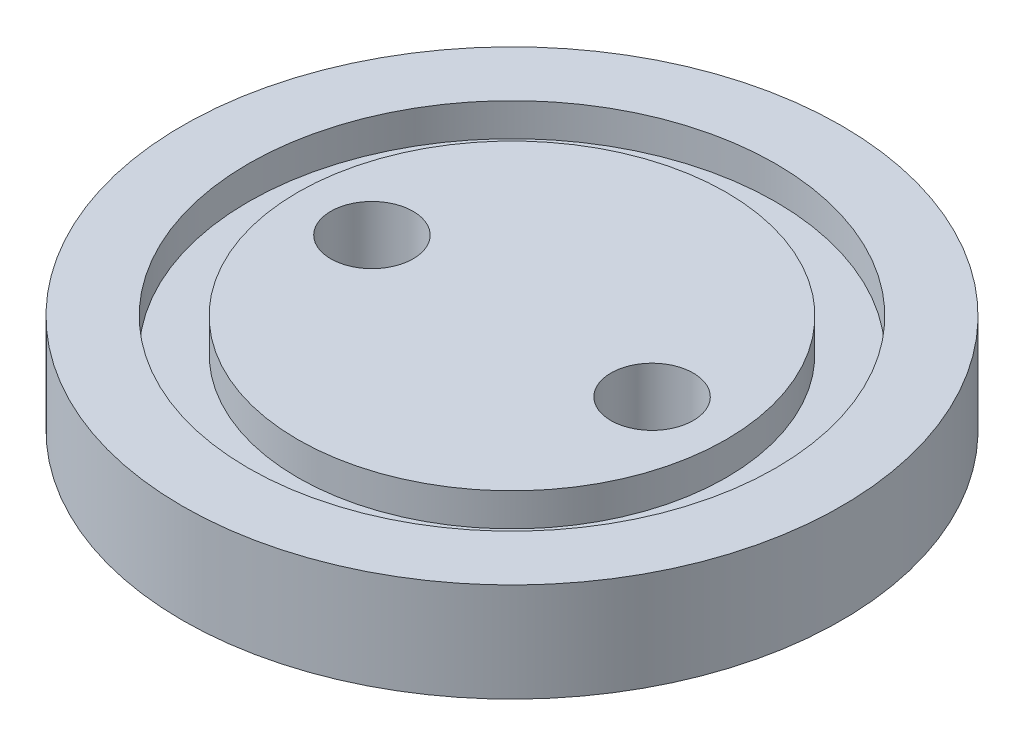
SolidWorks part; units mm, degrees
ref_plane "Front Plane" through (0, 0, 0) normal (0, 0, 1) x (1, 0, 0)
ref_plane "Top Plane" through (0, 0, 0) normal (0, 1, 0) x (1, 0, 0)
ref_plane "Right Plane" through (0, 0, 0) normal (1, 0, 0) x (0, 0, -1)
sketch "Sketch1" plane through (0, 0, 0) normal (0, 1, 0) x (1, 0, 0)
  line L0 (0, 6.5) -> (0, -6.5) construction
  circle A0 centre (0, 0) radius 10
  dimension "D1" = 20
extrude "Boss-Extrude1" add sketch "Sketch1" along normal blind 3
sketch "Sketch3" plane through (0, 3, 0) normal (0, 1, 0) x (1, 0, 0)
  circle A0 centre (0, 0) radius 8
  circle A1 centre (0, 0) radius 6.5
  dimension "D1" = 16
  dimension "D2" = 13
extrude "Cut-Extrude1" cut sketch "Sketch3" against normal blind 1
sketch "Sketch4" plane through (0, 0, 0) normal (0, 1, 0) x (1, 0, 0)
  line L0 (0, 6.5) -> (0, -6.5) construction
  line L1 (-4.25, 0) -> (4.25, 0) construction
  circle A2 centre (4.25, 0) radius 1.25
  circle A3 centre (0, 0) radius 6.5 construction
  circle A4 centre (0, 0) radius 6.5 construction
  circle A5 centre (-4.25, 0) radius 1.25
  dimension "D1" = 2.5
  dimension "D2" = 8.5
  dimension "D3" = 4.25
extrude "Cut-Extrude2" cut sketch "Sketch4" along normal through all
